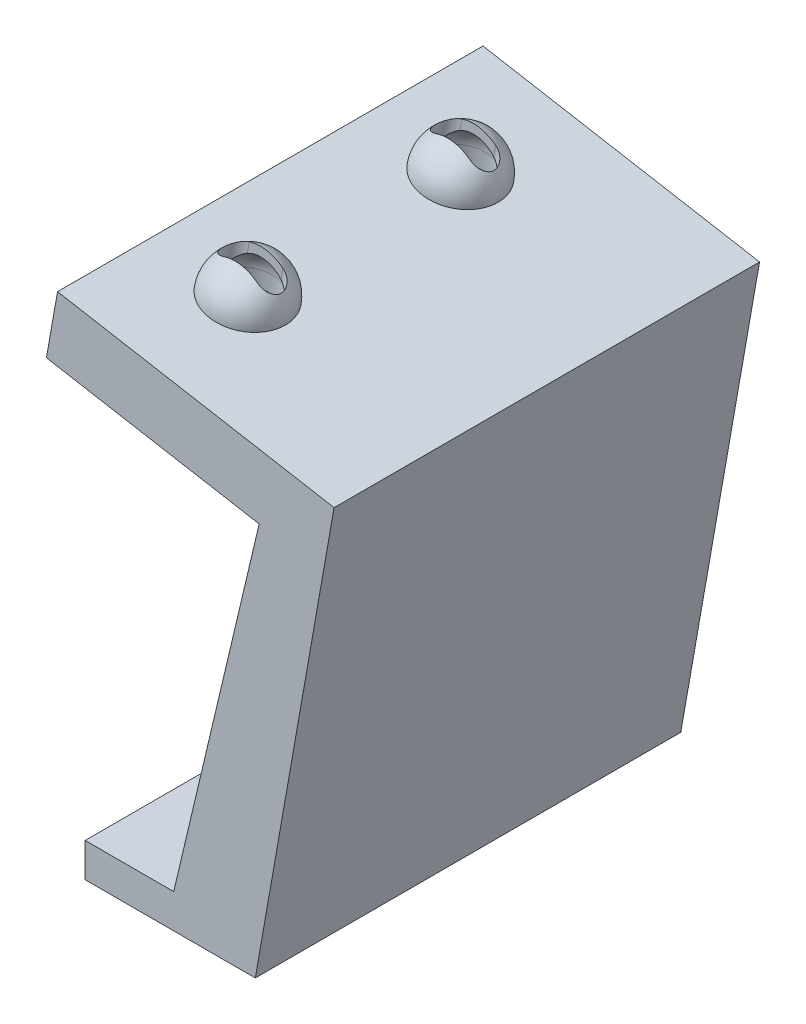
SolidWorks part; units mm, degrees
ref_plane "Front Plane" through (0, 0, 0) normal (0, 0, 1) x (1, 0, 0)
ref_plane "Top Plane" through (0, 0, 0) normal (0, 1, 0) x (1, 0, 0)
ref_plane "Right Plane" through (0, 0, 0) normal (1, 0, 0) x (0, 0, -1)
sketch "Sketch1" plane through (0, 0, 0) normal (0, 0, 1) x (1, 0, 0)
  line L1 (19.4718, 0) -> (37.9862, 105)
  line L2 (37.9862, 105) -> (-27.0138, 116.4613)
  line L3 (-27.0138, 116.4613) -> (-29.6185, 101.6891)
  line L4 (-29.6185, 101.6891) -> (20.3815, 92.8728)
  line L5 (20.3815, 92.8728) -> (0.2969, 8)
  line L7 (19.4718, 0) -> (-20.5282, 0)
  line L8 (-20.5282, 0) -> (-20.5282, 8)
  line L9 (-20.5282, 8) -> (0.2969, 8)
  dimension "D1" = 105
  dimension "D2" = 65
  dimension "D3" = 15
  dimension "D4" = 50
  dimension "D5" = 87.2169
  dimension "D6" = 100
  dimension "D7" = 8
  dimension "D8" = 40
  dimension "D9" = 20.5282
extrude "Boss-Extrude1" add sketch "Sketch1" along normal blind 100
ref_plane "Plane1" through (0, 0, 25) normal (0, 0, 1) x (1, 0, 0)
sketch "Sketch2" plane through (0, 0, 25) normal (0, 0, 1) x (1, 0, 0)
  line L0 (-2.813, 138.5355) -> (-11.4797, 89.3841) construction
  line L2 (37.9862, 105) -> (-27.0138, 116.4613) construction
  line L3 (-27.0138, 116.4613) -> (-29.6185, 101.6891) construction
  line L4 (-5.7403, 121.9338) -> (-6.0871, 119.9674)
  line L5 (-14.2108, 114.2037) -> (-16.1774, 114.5505)
  arc A0 (-5.7403, 121.9338) -> (-16.1774, 114.5505) centre (-7.3026, 113.0737) ccw
  arc A1 (-6.0871, 119.9674) -> (-14.2108, 114.2037) centre (-7.3026, 113.0737) ccw
  dimension "D2" = 7
  dimension "D3" = 8.9968
  dimension "D1" = 20
  dimension "D4" = 1.9969
revolve "Revolve1" add sketch "Sketch2" angle 360 about L0
sketch "Sketch6" plane through (0, 0, 25) normal (0, 0, 1) x (1, 0, 0)
  line L0 (-4.9456, 126.4409) -> (-12.8458, 81.6367) construction
  line L1 (37.9862, 105) -> (-27.0138, 116.4613) construction
  line L3 (-29.6185, 101.6891) -> (20.3815, 92.8728) construction
  line L4 (-7.665, 111.0187) -> (-9.9224, 98.2162)
  line L5 (-9.9224, 98.2162) -> (-22.7249, 100.4736)
  arc A0 (1.542, 111.4261) -> (-16.1774, 114.5505) centre (-7.3026, 113.0737) ccw construction
  arc A2 (-7.665, 111.0187) -> (-22.7249, 100.4736) centre (-9.9224, 98.2162) ccw
  dimension "D1" = 26
revolve "Cut-Revolve3" cut sketch "Sketch6" angle 360 about L0
sketch "Sketch7" plane through (0, 0, 0) normal (0, 1, 0) x (1, 0, 0)
  line L0 (0, 0) -> (0, -121.1899) construction
sketch "Sketch8" plane through (19.1015, 108.3299, 0) normal (0.1736, 0.9848, 0) x (0.9848, -0.1736, 0)
  circle A0 centre (-26.83, -25) radius 7
  point P2 (0, 0)
  point P5 (-4.105, -42.3396)
  dimension "D1" = 14
  dimension "D2" = 26.83
  dimension "D3" = 25
extrude "Cut-Extrude1" cut sketch "Sketch8" against normal up to next
sketch "Sketch9" plane through (19.1015, 108.3299, 0) normal (0.1736, 0.9848, 0) x (0.9848, -0.1736, 0)
  line L0 (-53.755, -25) -> (29.0865, -25) construction
  line L1 (-22.83, -25) -> (-30.83, -25) construction
  line L2 (-22.83, -28) -> (-30.83, -28)
  line L3 (-22.83, -22) -> (-30.83, -22)
  arc A0 (-22.83, -28) -> (-22.83, -22) centre (-22.83, -25) ccw
  arc A1 (-30.83, -22) -> (-30.83, -28) centre (-30.83, -25) ccw
  point P5 (-26.83, -25)
  point P10 (-28.7873, -25)
  point P14 (0, 0)
  point P15 (0, 0)
  point P16 (-28.4407, -25)
  point P17 (-26.855, -25)
  point P18 (0, 0)
  dimension "D3" = 3
  dimension "D1" = 25
  dimension "D2" = 8
  dimension "D4" = 26.83
extrude "Cut-Extrude2" cut sketch "Sketch9" along normal up to next
ref_plane "Plane2" through (0, 0, 50) normal (0, 0, 1) x (1, 0, 0)
sketch "Sketch10" plane through (0, 8, 0) normal (0, 1, 0) x (1, 0, 0)
  line L0 (-20.5282, -100) -> (-20.5282, 0) construction
  line L1 (-20.5282, 0) -> (19.4718, 0) construction
  circle A0 centre (-10.5282, -25) radius 3.5
  point P6 (-18.3586, -0.5873)
  dimension "D2" = 7
  dimension "D1" = 10
  dimension "D3" = 25
extrude "Cut-Extrude3" cut sketch "Sketch10" against normal up to next
mirror "Mirror1" about plane through (0, 0, 50) normal (0, 0, 1) of "Cut-Extrude3", "Revolve1", "Cut-Extrude1", "Cut-Extrude2", "Cut-Revolve3"
sketch "Sketch11" plane through (0, 0, 50) normal (0, 0, 1) x (1, 0, 0)
  line L0 (2.8801, 95.9587) -> (15.6488, 72.8739)
  line L1 (20.3815, 92.8728) -> (0.2969, 8) construction
  line L5 (-29.6185, 101.6891) -> (20.3815, 92.8728) construction
  line L6 (20.3815, 92.8728) -> (15.6488, 72.8739)
  line L7 (2.8801, 95.9587) -> (20.3815, 92.8728)
  dimension "D1" = 23.0849
extrude "Boss-Extrude2" add sketch "Sketch11" along normal mid plane 20
sketch "Sketch12" plane through (0, 0, 50) normal (0, 0, 1) x (1, 0, 0)
  line L0 (5.0297, 28) -> (-14.9135, 8)
  line L1 (20.3815, 92.8728) -> (0.2969, 8) construction
  line L2 (0.2969, 8) -> (-20.5282, 8) construction
  line L3 (-14.9135, 8) -> (0.2969, 8)
  line L4 (0.2969, 8) -> (5.0297, 28)
  dimension "D1" = 20
  dimension "D2" = 15.2104
extrude "Boss-Extrude3" add sketch "Sketch12" along normal mid plane 20
